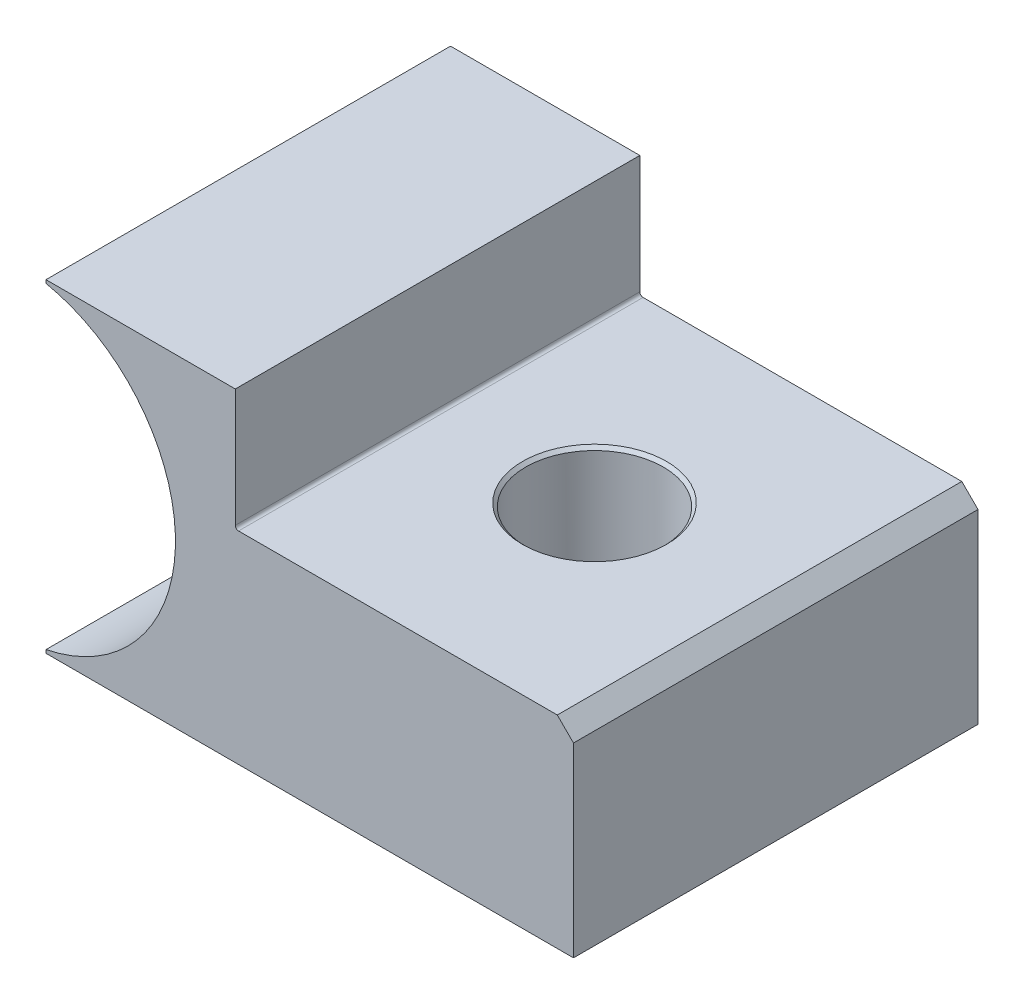
SolidWorks part; units mm, degrees
material "AISI Type A2 Tool Steel Custom"
ref_plane "Front Plane" through (0, 0, 0) normal (0, 0, 1) x (1, 0, 0)
ref_plane "Top Plane" through (0, 0, 0) normal (0, 1, 0) x (1, 0, 0)
ref_plane "Right Plane" through (0, 0, 0) normal (1, 0, 0) x (0, 0, -1)
sketch "Sketch1" plane through (0, 0, 0) normal (0, 0, 1) x (1, 0, 0)
  line L1 (2.54, 0) -> (43.942, 0)
  line L3 (2.54, 25.4) -> (17.399, 25.4)
  line L4 (43.942, 0) -> (43.942, 15.875)
  line L5 (2.54, 25.4) -> (2.54, 25.1434)
  line L6 (17.399, 25.4) -> (17.399, 15.875)
  line L7 (17.399, 15.875) -> (43.942, 15.875)
  line L8 (2.54, 0.2566) -> (2.54, 0)
  arc A1 (2.54, 0.2566) -> (2.54, 25.1434) centre (0, 12.7) ccw
  dimension "D2" = 25.4
  dimension "D1" = 14.859
  dimension "D3" = 9.525
  dimension "D4" = 2.54
  dimension "D5" = 26.543
  dimension "D6" = 15.875
  dimension "D7" = 0.2566
extrude "Boss-Extrude1" add sketch "Sketch1" along normal blind 31.75
sketch "Sketch5" plane through (0, 15.875, 0) normal (0, 1, 0) x (1, 0, 0)
  line L0 (0, -31.75) -> (0, 0) construction
  line L1 (2.54, -31.75) -> (2.54, 0) construction
  point P0 (29.718, -15.875)
  point P5 (0, -15.875)
  point P8 (2.54, -15.875)
  dimension "D1" = 29.718
hole_wizard "X (0.397) Diameter Hole1" positions "Sketch5" profile "Sketch4" hole size "X" standard "ANSI Inch" end condition through all
sketch "Sketch4" plane through (29.718, 15.875, 15.875) normal (1, 0, 0) x (0, 0, 1)
  line L0 (0, 0) -> (0, 15.875)
  line L1 (0, 15.875) -> (5.3975, 15.875)
  line L2 (5.3975, 15.875) -> (5.3975, 0)
  line L5 (5.3975, 0) -> (0, 0)
  line L11 (0, -6.35) -> (0, 107.95) construction
  dimension "Thru Hole Dia." = 10.795
  dimension "Thru Hole Depth" = 15.875
chamfer "Chamfer1" distance 1.27 angle 45 1 edges at (43.942, 15.875, 15.875)
chamfer "Chamfer2" distance 0.254 angle 45 1 edges at (29.718, 15.875, 21.2725)
fillet "Fillet1" radius 0.254 1 edges at (17.399, 15.875, 15.875)
